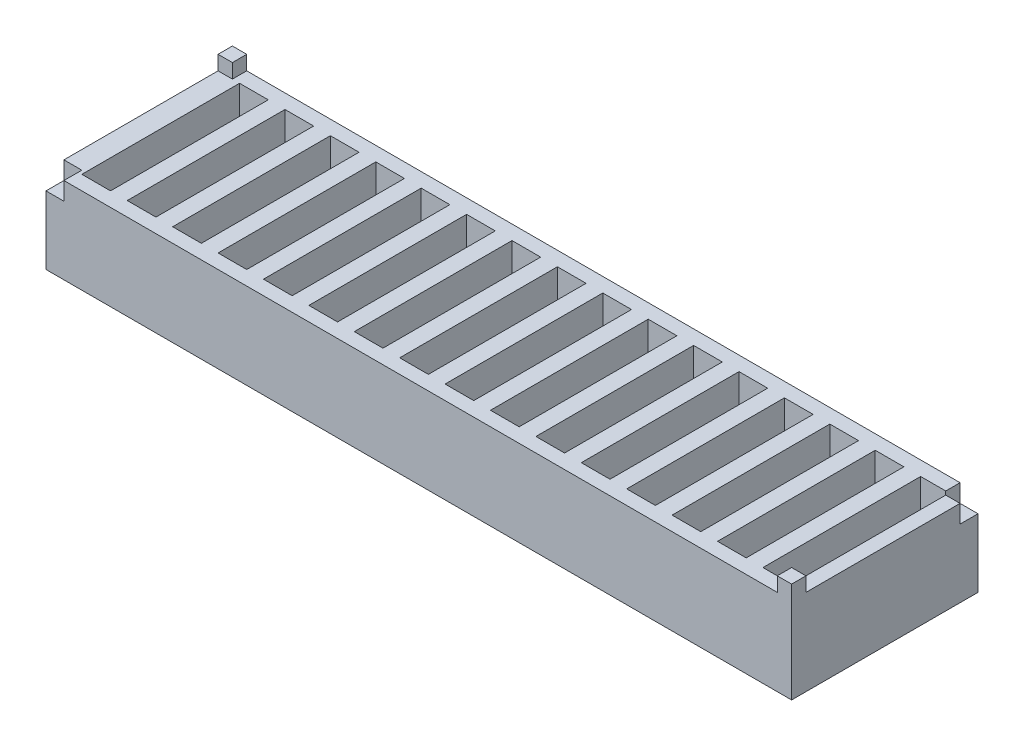
SolidWorks part; units mm, degrees
ref_plane "Front Plane" through (0, 0, 0) normal (0, 0, 1) x (1, 0, 0)
ref_plane "Top Plane" through (0, 0, 0) normal (0, 1, 0) x (1, 0, 0)
ref_plane "Right Plane" through (0, 0, 0) normal (1, 0, 0) x (0, 0, -1)
sketch "Sketch1" plane through (0, 0, 0) normal (0, 1, 0) x (1, 0, 0)
  line L1 (-52, -13) -> (52, -13)
  line L2 (-52, -13) -> (-52, 13)
  line L3 (-52, 13) -> (52, 13)
  line L4 (52, -13) -> (52, 13)
  line L5 (-52, -13) -> (52, 13) construction
  line L6 (-52, 13) -> (52, -13) construction
  point P0 (0, 0)
  dimension "D1" = 104
  dimension "D2" = 26
extrude "Boss-Extrude1" add sketch "Sketch1" along normal blind 12
sketch "Sketch2" plane through (0, 12, 0) normal (0, 1, 0) x (1, 0, 0)
  line L0 (-55, 0) -> (55, 0) construction
  line L1 (-49, 11) -> (-45, 11)
  line L2 (-49, 11) -> (-49, -11)
  line L3 (-49, -11) -> (-45, -11)
  line L4 (-45, 11) -> (-45, -11)
  line L5 (-52, 13) -> (-52, -13) construction
  line L6 (-38.6667, 11) -> (-38.6667, -11)
  line L7 (-42.6667, 11) -> (-38.6667, 11)
  line L8 (-42.6667, 11) -> (-42.6667, -11)
  line L9 (-42.6667, -11) -> (-38.6667, -11)
  line L10 (-32.3333, 11) -> (-32.3333, -11)
  line L11 (-36.3333, 11) -> (-32.3333, 11)
  line L12 (-36.3333, 11) -> (-36.3333, -11)
  line L13 (-36.3333, -11) -> (-32.3333, -11)
  line L14 (-26, 11) -> (-26, -11)
  line L15 (-30, 11) -> (-26, 11)
  line L16 (-30, 11) -> (-30, -11)
  line L17 (-30, -11) -> (-26, -11)
  line L18 (-19.6667, 11) -> (-19.6667, -11)
  line L19 (-23.6667, 11) -> (-19.6667, 11)
  line L20 (-23.6667, 11) -> (-23.6667, -11)
  line L21 (-23.6667, -11) -> (-19.6667, -11)
  line L22 (-13.3333, 11) -> (-13.3333, -11)
  line L23 (-17.3333, 11) -> (-13.3333, 11)
  line L24 (-17.3333, 11) -> (-17.3333, -11)
  line L25 (-17.3333, -11) -> (-13.3333, -11)
  line L26 (-7, 11) -> (-7, -11)
  line L27 (-11, 11) -> (-7, 11)
  line L28 (-11, 11) -> (-11, -11)
  line L29 (-11, -11) -> (-7, -11)
  line L30 (-0.6667, 11) -> (-0.6667, -11)
  line L31 (-4.6667, 11) -> (-0.6667, 11)
  line L32 (-4.6667, 11) -> (-4.6667, -11)
  line L33 (-4.6667, -11) -> (-0.6667, -11)
  line L34 (5.6667, 11) -> (5.6667, -11)
  line L35 (1.6667, 11) -> (5.6667, 11)
  line L36 (1.6667, 11) -> (1.6667, -11)
  line L37 (1.6667, -11) -> (5.6667, -11)
  line L38 (12, 11) -> (12, -11)
  line L39 (8, 11) -> (12, 11)
  line L40 (8, 11) -> (8, -11)
  line L41 (8, -11) -> (12, -11)
  line L42 (18.3333, 11) -> (18.3333, -11)
  line L43 (14.3333, 11) -> (18.3333, 11)
  line L44 (14.3333, 11) -> (14.3333, -11)
  line L45 (14.3333, -11) -> (18.3333, -11)
  line L46 (24.6667, 11) -> (24.6667, -11)
  line L47 (20.6667, 11) -> (24.6667, 11)
  line L48 (20.6667, 11) -> (20.6667, -11)
  line L49 (20.6667, -11) -> (24.6667, -11)
  line L50 (31, 11) -> (31, -11)
  line L51 (27, 11) -> (31, 11)
  line L52 (27, 11) -> (27, -11)
  line L53 (27, -11) -> (31, -11)
  line L54 (37.3333, 11) -> (37.3333, -11)
  line L55 (33.3333, 11) -> (37.3333, 11)
  line L56 (33.3333, 11) -> (33.3333, -11)
  line L57 (33.3333, -11) -> (37.3333, -11)
  line L58 (43.6667, 11) -> (43.6667, -11)
  line L59 (39.6667, 11) -> (43.6667, 11)
  line L60 (39.6667, 11) -> (39.6667, -11)
  line L61 (39.6667, -11) -> (43.6667, -11)
  line L62 (50, 11) -> (50, -11)
  line L63 (46, 11) -> (50, 11)
  line L64 (46, 11) -> (46, -11)
  line L65 (46, -11) -> (50, -11)
  line L66 (52, -13) -> (52, 13) construction
  dimension "D1" = 4
  dimension "D2" = 22
  dimension "D3" = 11
  dimension "D4" = 3
  dimension "D6" = 2
  dimension "D5" = 16
extrude "Cut-Extrude1" cut sketch "Sketch2" against normal blind 11
sketch "Sketch3" plane through (0, 12, 0) normal (0, 1, 0) x (1, 0, 0)
  line L1 (-52, 13) -> (-50, 13)
  line L2 (-52, 13) -> (-52, 11)
  line L3 (-52, 11) -> (-50, 11)
  line L4 (-50, 13) -> (-50, 11)
  line L6 (52, -13) -> (50, -13)
  line L7 (52, -13) -> (52, -11)
  line L8 (52, -11) -> (50, -11)
  line L9 (50, -13) -> (50, -11)
  dimension "D1" = 2
  dimension "D2" = 2
extrude "Boss-Extrude2" add sketch "Sketch3" along normal blind 2
sketch "Sketch4" plane through (0, 12, 0) normal (0, 1, 0) x (1, 0, 0)
  line L0 (-49, -11) -> (-45, -11) construction
  line L1 (-52, -13) -> (-49.5, -13)
  line L2 (-52, -13) -> (-52, -10.5)
  line L3 (-52, -10.5) -> (-49.5, -10.5)
  line L4 (-49.5, -13) -> (-49.5, -10.5)
  line L6 (52, 13) -> (49.5, 13)
  line L7 (52, 13) -> (52, 10.5)
  line L8 (52, 10.5) -> (49.5, 10.5)
  line L9 (49.5, 13) -> (49.5, 10.5)
  point P5 (-47, -11)
  dimension "D1" = 2.5
  dimension "D2" = 2.5
  dimension "D3" = 2.5
  dimension "D4" = 2.5
extrude "Cut-Extrude2" cut sketch "Sketch4" against normal blind 2.5
